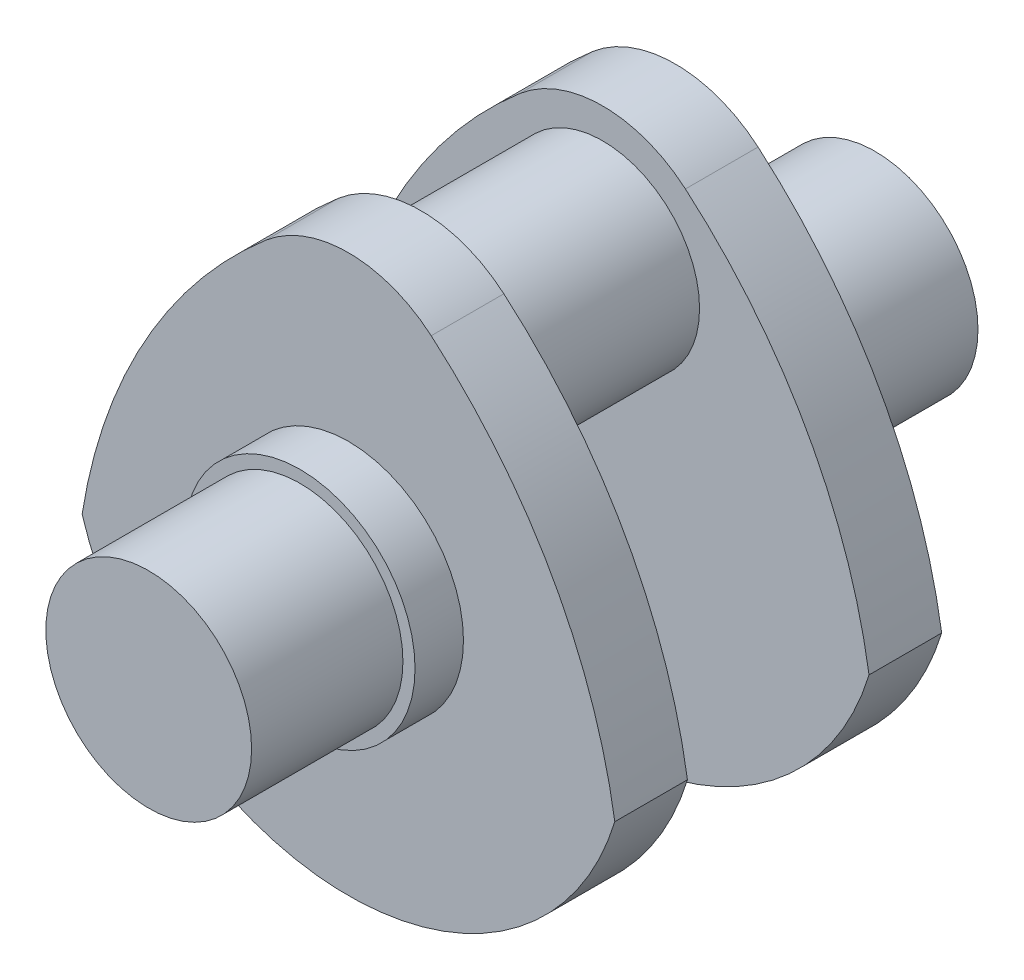
SolidWorks part; units mm, degrees
ref_plane "Front Plane" through (0, 0, 0) normal (0, 0, 1) x (1, 0, 0)
ref_plane "Top Plane" through (0, 0, 0) normal (0, 1, 0) x (1, 0, 0)
ref_plane "Right Plane" through (0, 0, 0) normal (1, 0, 0) x (0, 0, -1)
sketch "Sketch1" plane through (0, 0, 0) normal (0, 0, 1) x (1, 0, 0)
  circle A0 centre (0, 0) radius 17
  dimension "D1" = 34
extrude "Boss-Extrude1" add sketch "Sketch1" along normal blind 25
sketch "Sketch2" plane through (0, 0, 0) normal (0, 0, 1) x (1, 0, 0)
  circle A0 centre (0, 0) radius 19
  dimension "D1" = 38
extrude "Boss-Extrude2" add sketch "Sketch2" against normal blind 8
sketch "Sketch3" plane through (0, 0, -8) normal (0, 0, -1) x (-1, 0, 0)
  arc A0 (44, -13.4164) -> (-44, -13.4164) centre (0, 0) cw
  arc A1 (13.6681, 40.9431) -> (-13.6681, 40.9431) centre (0, 25) ccw
  arc A2 (-13.6681, 40.9431) -> (-44, -13.4164) centre (44.9095, -27.3845) ccw
  arc A3 (13.6681, 40.9431) -> (44, -13.4164) centre (-44.9095, -27.3845) cw
  dimension "D2" = 46
  dimension "D4" = 42
  dimension "D5" = 90
  dimension "D6" = 90
  dimension "D1" = 88
  dimension "D3" = 25
extrude "Boss-Extrude3" add sketch "Sketch3" along normal blind 12
sketch "Sketch4" plane through (0, 0, -20) normal (0, 0, -1) x (-1, 0, 0)
  circle A0 centre (0, 25) radius 16
  dimension "D1" = 32
  dimension "D2" = 25
extrude "Boss-Extrude4" add sketch "Sketch4" along normal blind 15
mirror "Mirror1" about plane through (0, 25, -35) normal (0, 0, -1) of bodies 104
